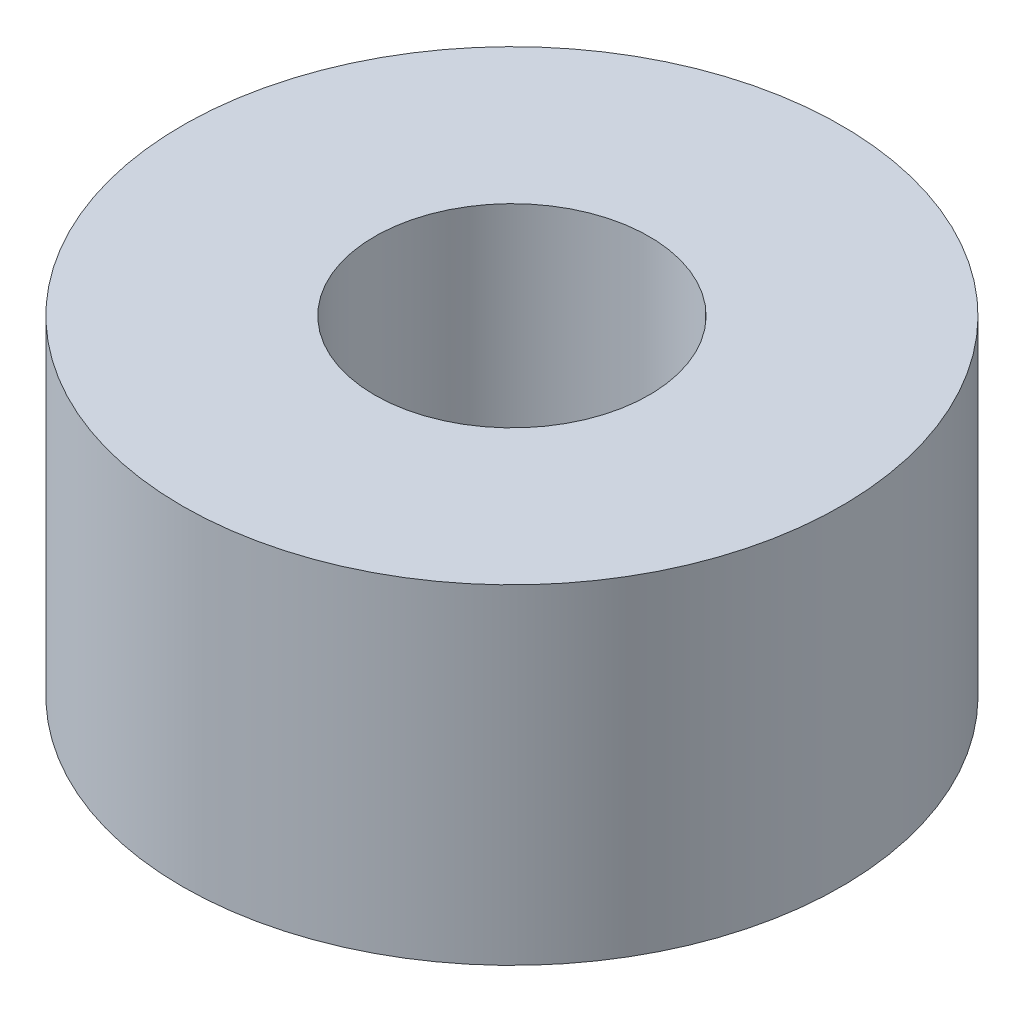
SolidWorks part; units mm, degrees
material "PA66 尼龙"
ref_plane "前视基准面" through (0, 0, 0) normal (0, 0, 1) x (1, 0, 0)
ref_plane "上视基准面" through (0, 0, 0) normal (0, 1, 0) x (1, 0, 0)
ref_plane "右视基准面" through (0, 0, 0) normal (1, 0, 0) x (0, 0, -1)
sketch "草图1" plane through (0, 0, 0) normal (0, 1, 0) x (1, 0, 0)
  circle A0 centre (0, 0) radius 3
  circle A1 centre (0, 0) radius 1.25
  dimension "D1" = 6
  dimension "D2" = 2.5
extrude "凸台-拉伸1" add sketch "草图1" along normal blind 3
